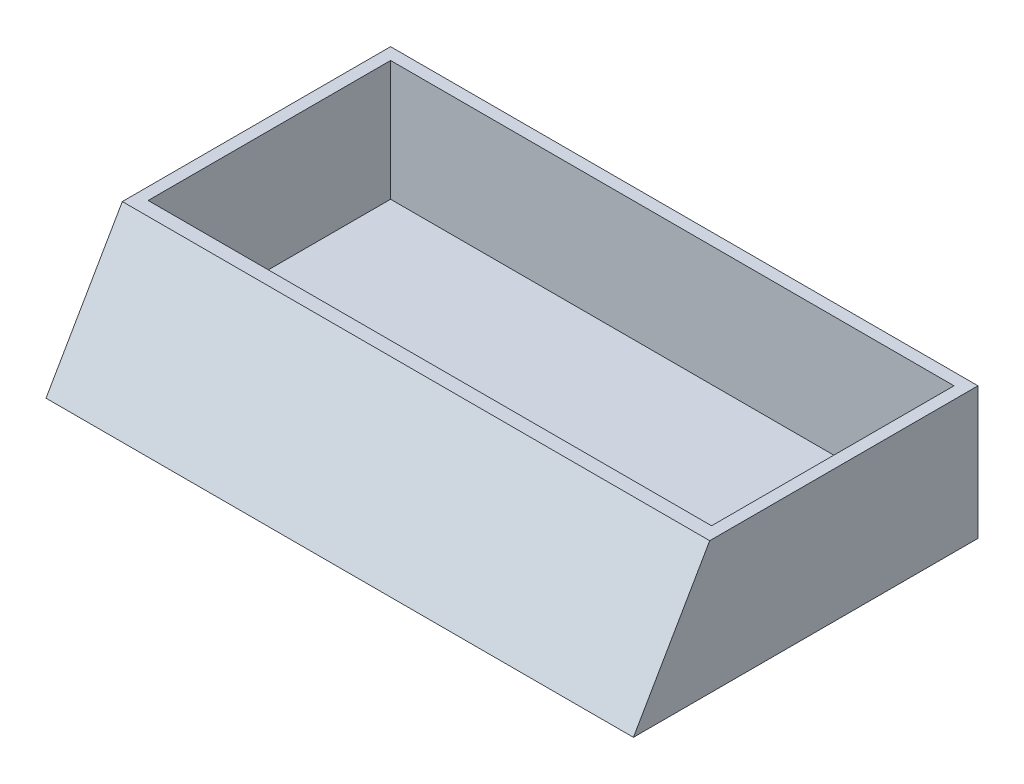
SolidWorks part; units mm, degrees
ref_plane "Alzado" through (0, 0, 0) normal (0, 0, 1) x (1, 0, 0)
ref_plane "Planta" through (0, 0, 0) normal (0, 1, 0) x (1, 0, 0)
ref_plane "Vista lateral" through (0, 0, 0) normal (1, 0, 0) x (0, 0, -1)
sketch "Croquis1" plane through (0, 0, 0) normal (1, 0, 0) x (0, 0, -1)
  line L0 (0, 0) -> (114.98, 0)
  line L1 (114.98, 0) -> (114.98, 44.1)
  line L2 (114.98, 44.1) -> (25.4611, 44.1)
  line L3 (0, 0) -> (25.4611, 44.1)
  line L4 (114.9845, -5.19) -> (114.9845, 15.0485) construction
  dimension "D1" = 114.98
  dimension "D2" = 44.1
  dimension "D3" = 120
extrude "Saliente-Extruir1" add sketch "Croquis1" along normal blind 196
shell "Vaciado1" thickness 4
